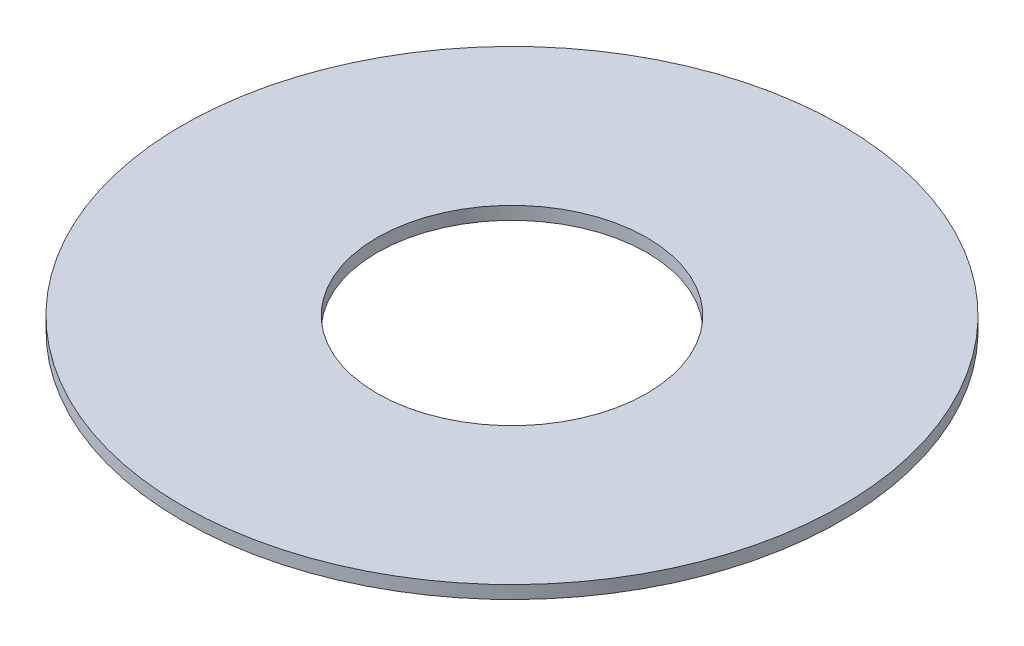
SolidWorks part; units mm, degrees
ref_plane "Спереди" through (0, 0, 0) normal (0, 0, 1) x (1, 0, 0)
ref_plane "Сверху" through (0, 0, 0) normal (0, 1, 0) x (1, 0, 0)
ref_plane "Справа" through (0, 0, 0) normal (1, 0, 0) x (0, 0, -1)
sketch "Эскиз1" plane through (0, 0, 0) normal (0, 1, 0) x (1, 0, 0)
  circle A0 centre (0, 0) radius 12.7
  circle A1 centre (0, 0) radius 5.2
extrude "Вытянуть1" add sketch "Эскиз1" along normal blind 0.5
